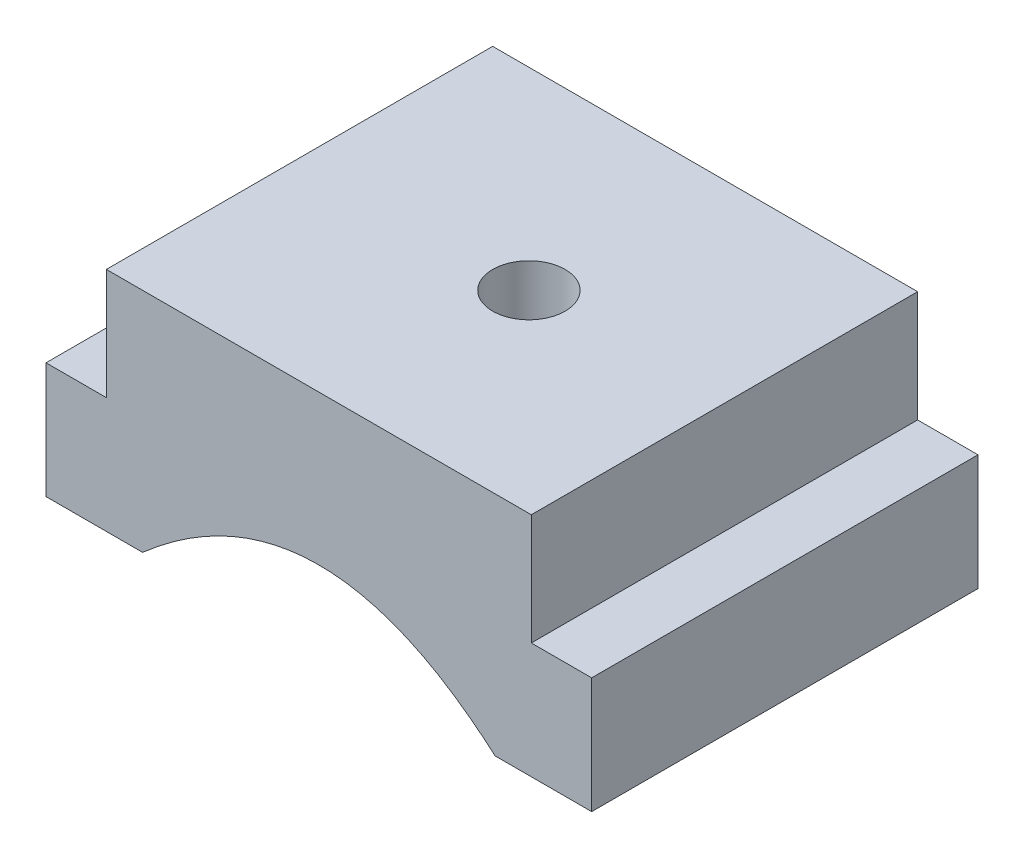
SolidWorks part; units mm, degrees
ref_plane "前视基准面" through (0, 0, 0) normal (0, 0, 1) x (1, 0, 0)
ref_plane "上视基准面" through (0, 0, 0) normal (0, 1, 0) x (1, 0, 0)
ref_plane "右视基准面" through (0, 0, 0) normal (1, 0, 0) x (0, 0, -1)
sketch "草图3" plane through (0, 0, 0) normal (0, 0, 1) x (1, 0, 0)
  line L0 (60.7028, 47) -> (-27.2972, 47)
  line L2 (-27.2972, 47) -> (-27.2972, 24)
  line L3 (-27.2972, 24) -> (-39.7972, 24)
  line L4 (-39.7972, 24) -> (-39.7972, 0)
  line L5 (55, 0) -> (-55, 0) construction
  line L7 (73.2028, 0) -> (73.2028, 24)
  line L8 (73.2028, 24) -> (60.7028, 24)
  line L9 (60.7028, 24) -> (60.7028, 47)
  line L10 (73.2028, 0) -> (53.2028, 0)
  line L11 (-39.7972, 0) -> (-19.7972, 0)
  spline S0 degree 2 poles (-19.7972, 0) (16.7028, 32) (53.2028, 0) knots 0 0 0 1 1 1
  point P3 (16.7028, 47)
  dimension "D1" = 88
  dimension "D2" = 24
  dimension "D3" = 23
  dimension "D4" = 12.5
  dimension "D5" = 23
  dimension "D6" = 12.5
  dimension "D7" = 20
  dimension "D8" = 20
  dimension "D9" = 31
extrude "凸台-拉伸1" add sketch "草图3" along normal blind 80
sketch "草图4" plane through (0, 47, 0) normal (0, 1, 0) x (1, 0, 0)
  line L0 (60.7028, 0) -> (-27.2972, 0) construction
  line L5 (-27.2972, -80) -> (-27.2972, 0) construction
  circle A0 centre (20.2028, -40) radius 7.5
  dimension "D1" = 15
  dimension "D2" = 40
  dimension "D3" = 47.5
extrude "切除-拉伸1" cut sketch "草图4" against normal through all
